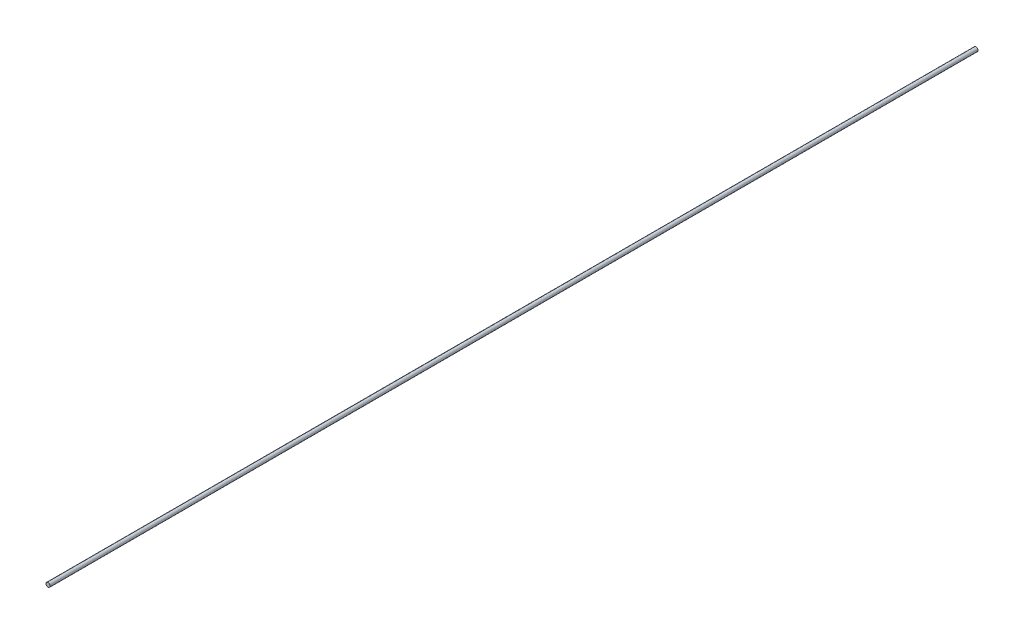
SolidWorks part; units mm, degrees
material "AISI 304"
ref_plane "Front Plane" through (0, 0, 0) normal (0, 0, 1) x (1, 0, 0)
ref_plane "Top Plane" through (0, 0, 0) normal (0, 1, 0) x (1, 0, 0)
ref_plane "Right Plane" through (0, 0, 0) normal (1, 0, 0) x (0, 0, -1)
sketch "Sketch1" plane through (0, 0, 0) normal (0, 0, 1) x (1, 0, 0)
  circle A0 centre (0, 0) radius 3
  dimension "D1" = 6
extrude "Boss-Extrude1" add sketch "Sketch1" along normal blind 1346.2
